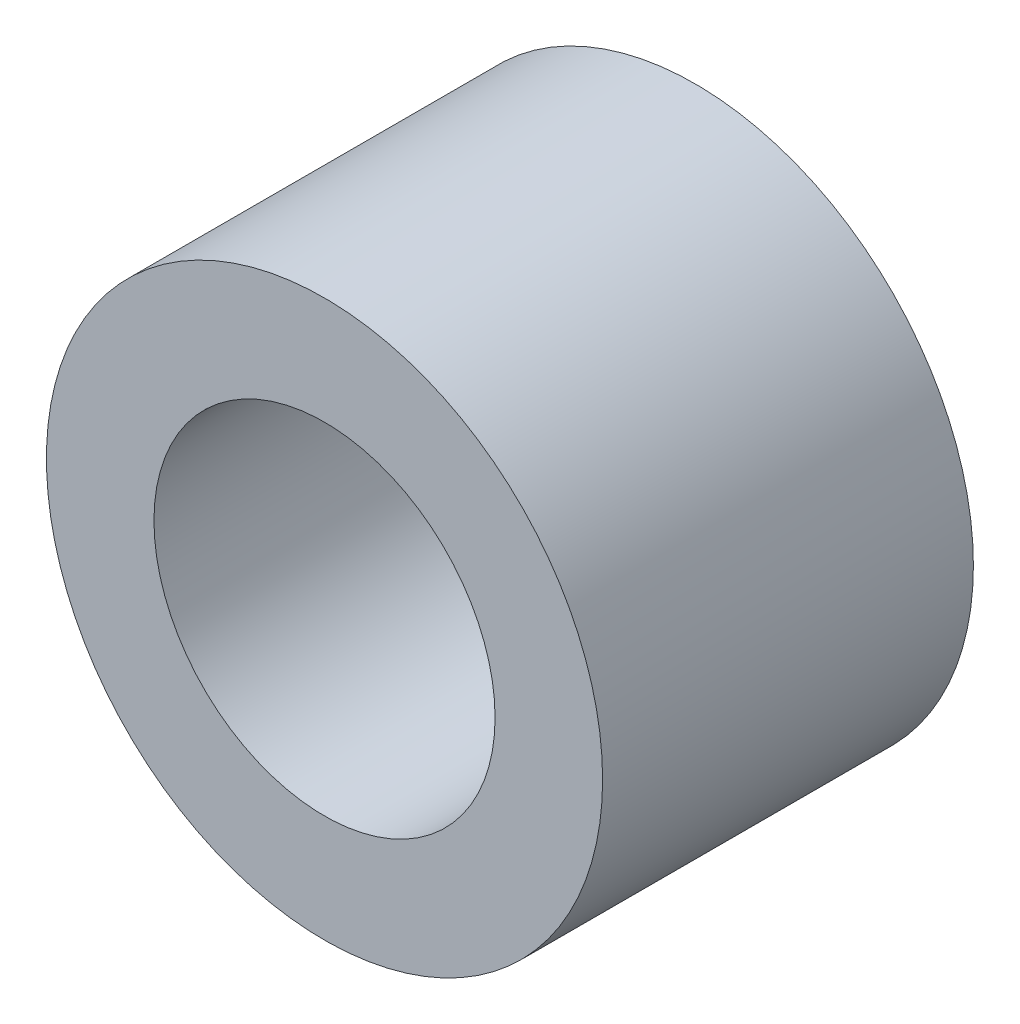
SolidWorks part; units mm, degrees
material "Nylon 101"
ref_plane "Front Plane" through (0, 0, 0) normal (0, 0, 1) x (1, 0, 0)
ref_plane "Top Plane" through (0, 0, 0) normal (0, 1, 0) x (1, 0, 0)
ref_plane "Right Plane" through (0, 0, 0) normal (1, 0, 0) x (0, 0, -1)
sketch "Sketch1" plane through (0, 0, 0) normal (0, 0, 1) x (1, 0, 0)
  circle A0 centre (0, 0) radius 2.3812
  circle A1 centre (0, 0) radius 1.4605
  dimension "OD" = 4.7625
  dimension "ID" = 2.921
extrude "Extrude1" add sketch "Sketch1" along normal mid plane 3.175
sketch "Sketch2" plane through (0, 0, 0) normal (1, 0, 0) x (0, 0, -1)
  line L0 (-1.5875, -1.4605) -> (1.5875, -1.4605) construction
  line L3 (1.5875, 1.4605) -> (-1.5875, 1.4605) construction
  line L5 (-1.5875, -1.4605) -> (1.5875, -1.4605)
  line L6 (1.5875, 1.4605) -> (-1.5875, 1.4605)
sketch "Sketch4" plane through (0, 0, 1.5875) normal (0, 0, 1) x (1, 0, 0)
  line L0 (0, 0) -> (-1.0327, 1.0327)
  line L1 (0, -2.1828) -> (0, 2.1828) construction
  circle A0 centre (0, 0) radius 1.4605 construction
  dimension "D1" = 45
